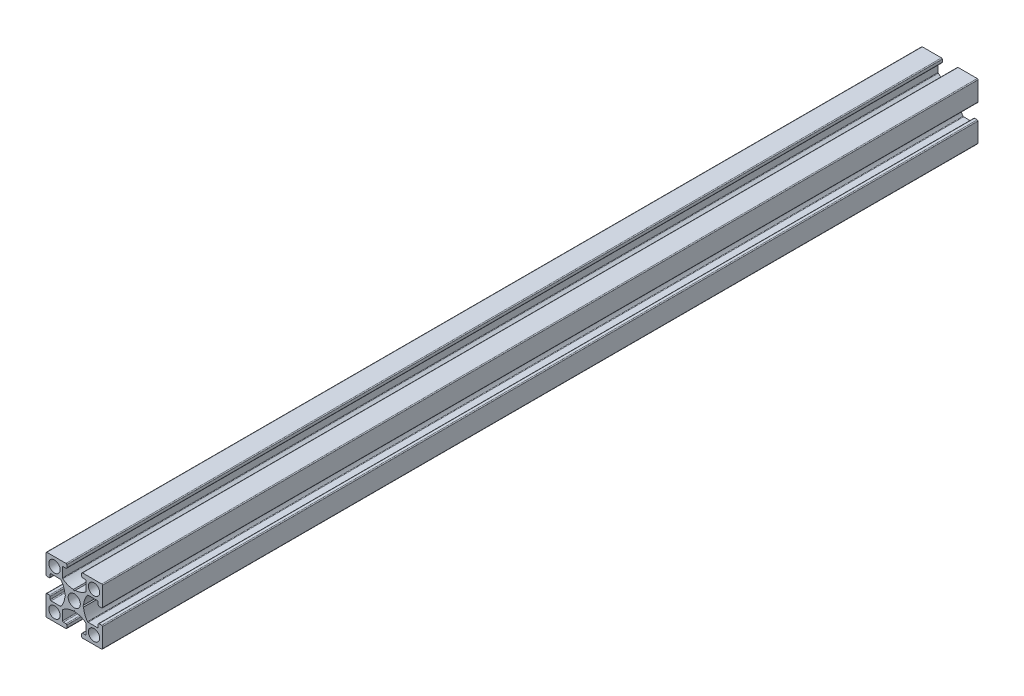
SolidWorks part; units mm, degrees
ref_plane "정면" through (0, 0, 0) normal (0, 0, 1) x (1, 0, 0)
ref_plane "윗면" through (0, 0, 0) normal (0, 1, 0) x (1, 0, 0)
ref_plane "우측면" through (0, 0, 0) normal (1, 0, 0) x (0, 0, -1)
sketch "Model" plane through (0, 0, 0) normal (0, 0, 1) x (1, 0, 0)
  line L0 (2307.7639, 1192.1343) -> (2307.7639, 1195.3915)
  line L1 (2307.4639, 1195.6915) -> (2306.5639, 1195.6915)
  line L2 (2306.2639, 1195.9915) -> (2306.2639, 1196.8915)
  line L3 (2306.5639, 1197.1915) -> (2313.3139, 1197.1915)
  line L4 (2313.6139, 1196.8915) -> (2313.6139, 1190.1415)
  line L5 (2313.3139, 1189.8415) -> (2312.4139, 1189.8415)
  line L6 (2312.1139, 1190.1415) -> (2312.1139, 1191.0415)
  line L7 (2311.8139, 1191.3415) -> (2308.5567, 1191.3415)
  line L8 (2306.9212, 1187.4988) -> (2306.6139, 1187.1915)
  line L9 (2306.6139, 1187.1915) -> (2306.9212, 1186.8843)
  line L10 (2308.5567, 1183.0415) -> (2311.8139, 1183.0415)
  line L11 (2312.1139, 1183.3415) -> (2312.1139, 1184.2415)
  line L12 (2312.4139, 1184.5415) -> (2313.3139, 1184.5415)
  line L13 (2313.6139, 1184.2415) -> (2313.6139, 1177.4915)
  line L14 (2313.3139, 1177.1915) -> (2306.5639, 1177.1915)
  line L15 (2306.2639, 1177.4915) -> (2306.2639, 1178.3915)
  line L16 (2306.5639, 1178.6915) -> (2307.4639, 1178.6915)
  line L17 (2307.7639, 1178.9915) -> (2307.7639, 1182.2488)
  line L18 (2303.9212, 1183.8843) -> (2303.6139, 1184.1915)
  line L19 (2303.6139, 1184.1915) -> (2303.3066, 1183.8843)
  line L20 (2299.4639, 1182.2488) -> (2299.4639, 1178.9915)
  line L21 (2299.7639, 1178.6915) -> (2300.6639, 1178.6915)
  line L22 (2300.9639, 1178.3915) -> (2300.9639, 1177.4915)
  line L23 (2300.6639, 1177.1915) -> (2293.9139, 1177.1915)
  line L24 (2293.6139, 1177.4915) -> (2293.6139, 1184.2415)
  line L25 (2293.9139, 1184.5415) -> (2294.8139, 1184.5415)
  line L26 (2295.1139, 1184.2415) -> (2295.1139, 1183.3415)
  line L27 (2295.4139, 1183.0415) -> (2298.6712, 1183.0415)
  line L28 (2300.3066, 1186.8843) -> (2300.6139, 1187.1915)
  line L29 (2300.6139, 1187.1915) -> (2300.3066, 1187.4988)
  line L30 (2298.6712, 1191.3415) -> (2295.4139, 1191.3415)
  line L31 (2295.1139, 1191.0415) -> (2295.1139, 1190.1415)
  line L32 (2294.8139, 1189.8415) -> (2293.9139, 1189.8415)
  line L33 (2293.6139, 1190.1415) -> (2293.6139, 1196.8915)
  line L34 (2293.9139, 1197.1915) -> (2300.6639, 1197.1915)
  line L35 (2300.9639, 1196.8915) -> (2300.9639, 1195.9915)
  line L36 (2300.6639, 1195.6915) -> (2299.7639, 1195.6915)
  line L37 (2299.4639, 1195.3915) -> (2299.4639, 1192.1343)
  line L38 (2303.3066, 1190.4988) -> (2303.6139, 1190.1915)
  line L39 (2303.6139, 1190.1915) -> (2303.9212, 1190.4988)
  circle A0 centre (2303.6139, 1187.1915) radius 2.15
  circle A1 centre (2296.6139, 1194.1915) radius 2
  circle A2 centre (2296.6139, 1180.1915) radius 2
  circle A3 centre (2310.6139, 1194.1915) radius 2
  circle A4 centre (2310.6139, 1180.1915) radius 2
  arc A5 (2307.7639, 1195.3915) -> (2307.4639, 1195.6915) centre (2307.4639, 1195.3915) ccw
  arc A6 (2306.2639, 1195.9915) -> (2306.5639, 1195.6915) centre (2306.5639, 1195.9915) ccw
  arc A7 (2306.5639, 1197.1915) -> (2306.2639, 1196.8915) centre (2306.5639, 1196.8915) ccw
  arc A8 (2313.6139, 1196.8915) -> (2313.3139, 1197.1915) centre (2313.3139, 1196.8915) ccw
  arc A9 (2313.3139, 1189.8415) -> (2313.6139, 1190.1415) centre (2313.3139, 1190.1415) ccw
  arc A10 (2312.1139, 1190.1415) -> (2312.4139, 1189.8415) centre (2312.4139, 1190.1415) ccw
  arc A11 (2312.1139, 1191.0415) -> (2311.8139, 1191.3415) centre (2311.8139, 1191.0415) ccw
  arc A12 (2308.5567, 1191.3415) -> (2308.3217, 1191.2281) centre (2308.5567, 1191.0415) ccw
  arc A13 (2308.3217, 1191.2281) -> (2306.9212, 1187.4988) centre (2313.4048, 1187.1915) ccw
  arc A14 (2306.9212, 1186.8843) -> (2308.3217, 1183.155) centre (2313.4048, 1187.1915) ccw
  arc A15 (2308.3217, 1183.155) -> (2308.5567, 1183.0415) centre (2308.5567, 1183.3415) ccw
  arc A16 (2311.8139, 1183.0415) -> (2312.1139, 1183.3415) centre (2311.8139, 1183.3415) ccw
  arc A17 (2312.4139, 1184.5415) -> (2312.1139, 1184.2415) centre (2312.4139, 1184.2415) ccw
  arc A18 (2313.6139, 1184.2415) -> (2313.3139, 1184.5415) centre (2313.3139, 1184.2415) ccw
  arc A19 (2313.3139, 1177.1915) -> (2313.6139, 1177.4915) centre (2313.3139, 1177.4915) ccw
  arc A20 (2306.2639, 1177.4915) -> (2306.5639, 1177.1915) centre (2306.5639, 1177.4915) ccw
  arc A21 (2306.5639, 1178.6915) -> (2306.2639, 1178.3915) centre (2306.5639, 1178.3915) ccw
  arc A22 (2307.4639, 1178.6915) -> (2307.7639, 1178.9915) centre (2307.4639, 1178.9915) ccw
  arc A23 (2307.7639, 1182.2488) -> (2307.6505, 1182.4837) centre (2307.4639, 1182.2488) ccw
  arc A24 (2307.6505, 1182.4837) -> (2303.9212, 1183.8843) centre (2303.6139, 1177.4007) ccw
  arc A25 (2303.3066, 1183.8843) -> (2299.5774, 1182.4837) centre (2303.6139, 1177.4007) ccw
  arc A26 (2299.5774, 1182.4837) -> (2299.4639, 1182.2488) centre (2299.7639, 1182.2488) ccw
  arc A27 (2299.4639, 1178.9915) -> (2299.7639, 1178.6915) centre (2299.7639, 1178.9915) ccw
  arc A28 (2300.9639, 1178.3915) -> (2300.6639, 1178.6915) centre (2300.6639, 1178.3915) ccw
  arc A29 (2300.6639, 1177.1915) -> (2300.9639, 1177.4915) centre (2300.6639, 1177.4915) ccw
  arc A30 (2293.6139, 1177.4915) -> (2293.9139, 1177.1915) centre (2293.9139, 1177.4915) ccw
  arc A31 (2293.9139, 1184.5415) -> (2293.6139, 1184.2415) centre (2293.9139, 1184.2415) ccw
  arc A32 (2295.1139, 1184.2415) -> (2294.8139, 1184.5415) centre (2294.8139, 1184.2415) ccw
  arc A33 (2295.1139, 1183.3415) -> (2295.4139, 1183.0415) centre (2295.4139, 1183.3415) ccw
  arc A34 (2298.6712, 1183.0415) -> (2298.9061, 1183.155) centre (2298.6712, 1183.3415) ccw
  arc A35 (2298.9061, 1183.155) -> (2300.3066, 1186.8843) centre (2293.8231, 1187.1915) ccw
  arc A36 (2300.3066, 1187.4988) -> (2298.9061, 1191.2281) centre (2293.8231, 1187.1915) ccw
  arc A37 (2298.9061, 1191.2281) -> (2298.6712, 1191.3415) centre (2298.6712, 1191.0415) ccw
  arc A38 (2295.4139, 1191.3415) -> (2295.1139, 1191.0415) centre (2295.4139, 1191.0415) ccw
  arc A39 (2294.8139, 1189.8415) -> (2295.1139, 1190.1415) centre (2294.8139, 1190.1415) ccw
  arc A40 (2293.6139, 1190.1415) -> (2293.9139, 1189.8415) centre (2293.9139, 1190.1415) ccw
  arc A41 (2293.9139, 1197.1915) -> (2293.6139, 1196.8915) centre (2293.9139, 1196.8915) ccw
  arc A42 (2300.9639, 1196.8915) -> (2300.6639, 1197.1915) centre (2300.6639, 1196.8915) ccw
  arc A43 (2300.6639, 1195.6915) -> (2300.9639, 1195.9915) centre (2300.6639, 1195.9915) ccw
  arc A44 (2299.7639, 1195.6915) -> (2299.4639, 1195.3915) centre (2299.7639, 1195.3915) ccw
  arc A45 (2299.4639, 1192.1343) -> (2299.5774, 1191.8994) centre (2299.7639, 1192.1343) ccw
  arc A46 (2299.5774, 1191.8994) -> (2303.3066, 1190.4988) centre (2303.6139, 1196.9824) ccw
  arc A47 (2303.9212, 1190.4988) -> (2307.6505, 1191.8994) centre (2303.6139, 1196.9824) ccw
  arc A48 (2307.6505, 1191.8994) -> (2307.7639, 1192.1343) centre (2307.4639, 1192.1343) ccw
extrude "보스-돌출1" add sketch "Model" along normal blind 310
sketch "스케치1" plane through (0, 1197.1915, 0) normal (0, 1, 0) x (1, 0, 0)
  line L0 (2303.6139, -310) -> (2303.6139, 0) construction
  line L1 (2313.3139, 0) -> (2306.5639, 0) construction
  line L2 (2313.3139, -310) -> (2306.5639, -310) construction
  circle A0 centre (2303.6139, -30) radius 2.5
  circle A1 centre (2303.6139, -60) radius 2.5
  circle A2 centre (2303.6139, -155) radius 2.5
  circle A3 centre (2303.6139, -90) radius 2.5
  circle A4 centre (2303.6139, -220) radius 2.5
  circle A5 centre (2303.6139, -250) radius 2.5
  circle A6 centre (2303.6139, -280) radius 2.5
  point P20 (2309.9389, -310)
  dimension "D1" = 30
  dimension "D2" = 30
  dimension "D3" = 60
  dimension "D4" = 60
  dimension "D5" = 90
  dimension "D6" = 90
extrude "컷-돌출1" cut sketch "스케치1" against normal through all
